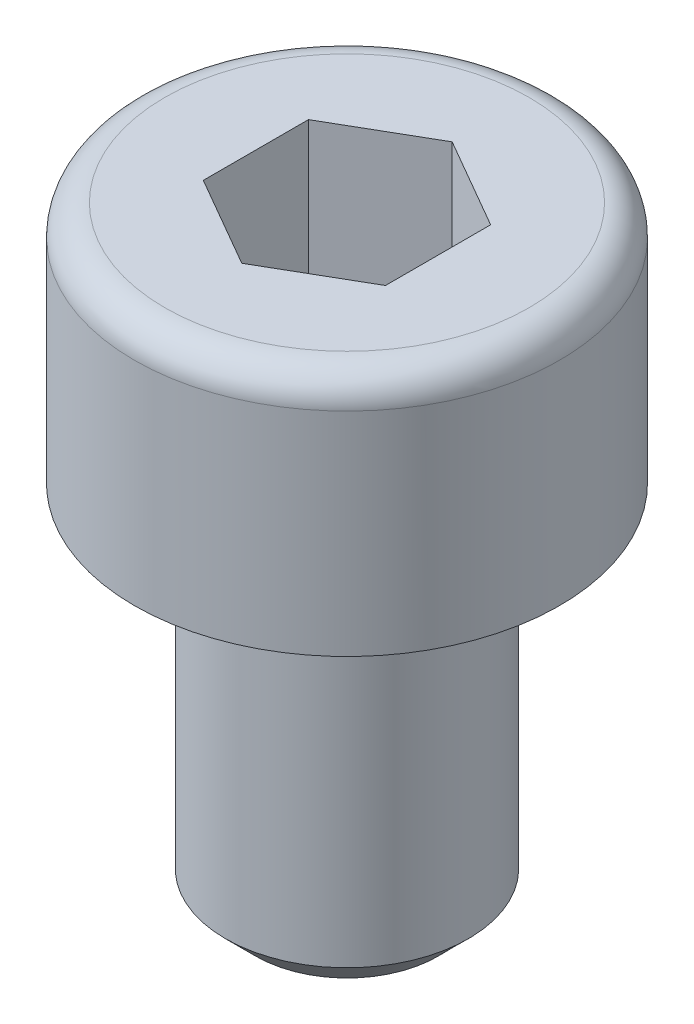
SolidWorks part; units mm, degrees
material "acero"
ref_plane "Alzado" through (0, 0, 0) normal (0, 0, 1) x (1, 0, 0)
ref_plane "Planta" through (0, 0, 0) normal (0, 1, 0) x (1, 0, 0)
ref_plane "Vista lateral" through (0, 0, 0) normal (1, 0, 0) x (0, 0, -1)
sketch "Croquis1" plane through (0, 0, 0) normal (0, 0, 1) x (1, 0, 0)
  line L0 (0, 0) -> (0, -60.9498) construction
  line L1 (0, 0) -> (3.5, 0)
  line L2 (3.5, 0) -> (3.5, -4)
  line L3 (3.5, -4) -> (2, -4)
  line L4 (2, -4) -> (2, -10)
  line L5 (2, -10) -> (0, -10)
  line L6 (0, -10) -> (0, 0)
  dimension "D1" = 6
  dimension "D2" = 4
  dimension "D3" = 7
  dimension "D4" = 4
revolve "Revolución1" add sketch "Croquis1" angle 360 about L0
sketch "Croquis2" plane through (0, 0, 0) normal (0, 1, 0) x (1, 0, 0)
  line L1 (1.5, 0.866) -> (0, 1.7321)
  line L2 (0, 1.7321) -> (-1.5, 0.866)
  line L3 (-1.5, 0.866) -> (-1.5, -0.866)
  line L4 (-1.5, -0.866) -> (0, -1.7321)
  line L5 (0, -1.7321) -> (1.5, -0.866)
  line L6 (1.5, -0.866) -> (1.5, 0.866)
  circle A0 centre (0, 0) radius 1.5 construction
  dimension "D1" = 3
extrude "Cortar-Extruir1" cut sketch "Croquis2" against normal blind 3
chamfer "Chaflán1" distance 0.5 angle 45
fillet "Redondeo1" radius 0.5
